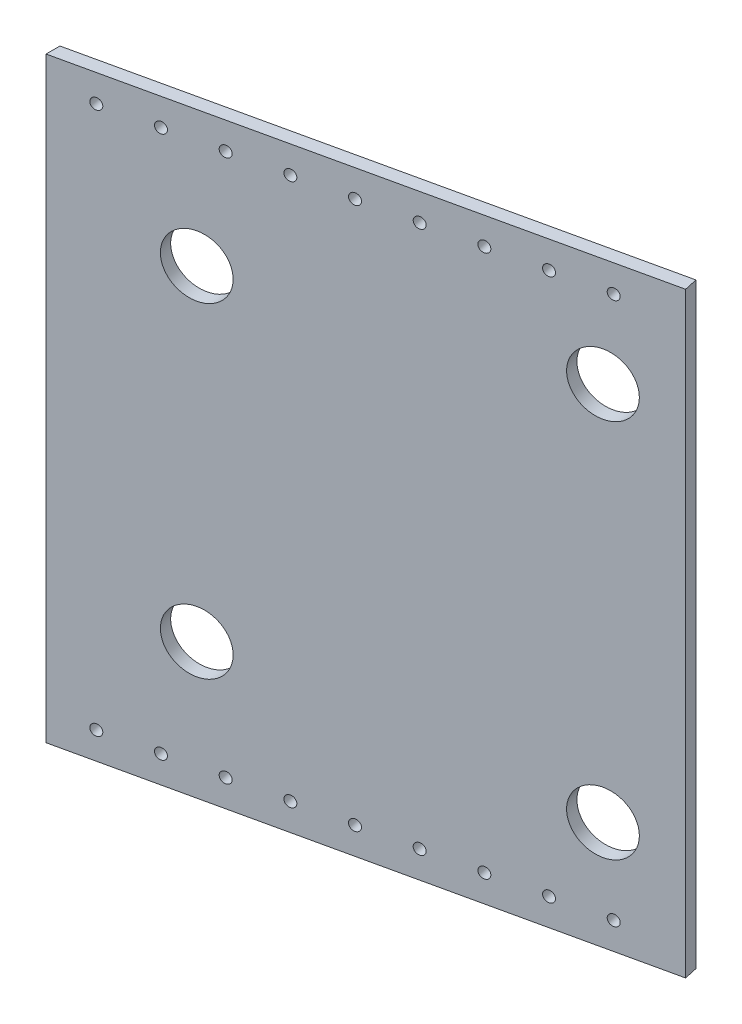
SolidWorks part; units mm, degrees
ref_plane "Front Plane" through (0, 0, 0) normal (0, 0, 1) x (1, 0, 0)
ref_plane "Top Plane" through (0, 0, 0) normal (0, 1, 0) x (1, 0, 0)
ref_plane "Right Plane" through (0, 0, 0) normal (1, 0, 0) x (0, 0, -1)
ref_plane "Plane1" through (191.2542, 0, 862.6918) normal (0.2164, 0, 0.9763) x (0, 1, 0)
sketch "Sketch1" plane through (191.2542, 0, 862.6918) normal (0.2164, 0, 0.9763) x (0, 1, 0)
  line L0 (6.35, -540.635) -> (284.48, -540.635)
  line L1 (284.48, -540.635) -> (284.48, -289.4438)
  line L2 (284.48, -289.4438) -> (6.35, -289.4438)
  line L3 (6.35, -289.4438) -> (6.35, -540.635)
extrude "Boss-Extrude1" add sketch "Sketch1" against normal blind 6.35
draft "Draft1" type of draft neutral plane draft angle 12.5 faces to draft 1 face at (473.1498, 145.415, 796.945) neutral plane through (191.2542, 0, 862.6918) neutral plane normal (0.2164, 0, 0.9763) reverse direction yes parameters "D1"=12.5
hole_wizard "Hole1" positions "Sketch3" profile "Sketch2" legacy
sketch "Sketch3" plane through (191.2542, 0, 862.6918) normal (0.2164, 0, 0.9763) x (0.9763, 0, -0.2164)
  point P0 (348.6301, 222.25)
  point P1 (508.1661, 234.95)
  point P2 (508.1661, 57.15)
  point P3 (348.6301, 69.85)
sketch "Sketch2" plane through (531.6203, 222.25, 787.2345) normal (0, 1, 0) x (0.9763, 0, -0.2164)
  line L0 (0, 0) -> (0, 59.1315)
  line L1 (0, 59.1315) -> (14.2875, 59.1315)
  line L2 (14.2875, 59.1315) -> (14.2875, 0)
  line L3 (14.2875, 0) -> (0, 0)
  line L4 (0, 110) -> (0, -10) construction
  dimension "Diameter" = 28.575
  dimension "Depth" = 59.1315
hole_wizard "#7 (0.201) Diameter Hole1" positions "Sketch5" profile "Sketch4" hole size "#7" standard "ANSI Inch"
sketch "Sketch5" plane through (191.2542, 0, 862.6918) normal (0.2164, 0, 0.9763) x (0.9763, 0, -0.2164)
  line L0 (512.3821, 273.05) -> (486.9821, 273.05) construction
  line L1 (486.9821, 273.05) -> (461.5821, 273.05) construction
  line L2 (461.5821, 273.05) -> (436.1821, 273.05) construction
  line L3 (436.1821, 273.05) -> (410.7821, 273.05) construction
  line L4 (410.7821, 273.05) -> (385.3821, 273.05) construction
  line L5 (385.3821, 273.05) -> (359.9821, 273.05) construction
  line L6 (359.9821, 273.05) -> (334.5821, 273.05) construction
  line L7 (334.5821, 273.05) -> (309.1821, 273.05) construction
  line L8 (309.1821, 273.05) -> (289.4438, 273.05) construction
  line L9 (289.4438, 284.48) -> (289.4438, 6.35) construction
  line L11 (540.635, 284.48) -> (289.4438, 284.48) construction
  point P0 (359.9821, 273.05)
  point P1 (410.7821, 273.05)
  point P2 (461.5821, 273.05)
  point P3 (512.3821, 273.05)
  point P4 (486.9821, 273.05)
  point P5 (436.1821, 273.05)
  point P6 (385.3821, 273.05)
  point P7 (334.5821, 273.05)
  point P8 (512.3826, 19.05)
  point P9 (486.9826, 19.05)
  point P10 (461.5826, 19.05)
  point P11 (436.1826, 19.05)
  point P12 (410.7826, 19.05)
  point P13 (385.3826, 19.05)
  point P14 (359.9826, 19.05)
  point P15 (334.5826, 19.05)
  point P16 (309.1826, 19.05)
  point P17 (309.1821, 273.05)
  dimension "D1" = 25.4
  dimension "D2" = 19.7383
  dimension "D3" = 11.43
sketch "Sketch4" plane through (542.7033, 273.05, 784.7774) normal (0, 1, 0) x (0.9763, 0, -0.2164)
  line L0 (0, 0) -> (0, 59.1315)
  line L1 (0, 59.1315) -> (2.5527, 59.1315)
  line L2 (2.5527, 59.1315) -> (2.5527, 0)
  line L5 (2.5527, 0) -> (0, 0)
  line L11 (0, -6.35) -> (0, 107.95) construction
  dimension "Thru Hole Dia." = 5.1054
  dimension "Thru Hole Depth" = 59.1315
sketch "Sketch6" plane through (0, 284.48, 0) normal (0, 1, 0) x (1, 0, 0)
  line L0 (473.837, -800.0447) -> (473.837, -793.5405)
  line L1 (717.6996, -739.4775) -> (473.837, -793.5405) construction
  line L2 (473.837, -793.5405) -> (473.837, -800.0447) construction
  line L3 (473.837, -793.5405) -> (717.6996, -739.4775)
  line L4 (717.6996, -739.4775) -> (719.074, -745.677)
  line L5 (719.074, -745.677) -> (473.837, -800.0447)
extrude "Boss-Extrude2" add sketch "Sketch6" along normal blind 1.27
